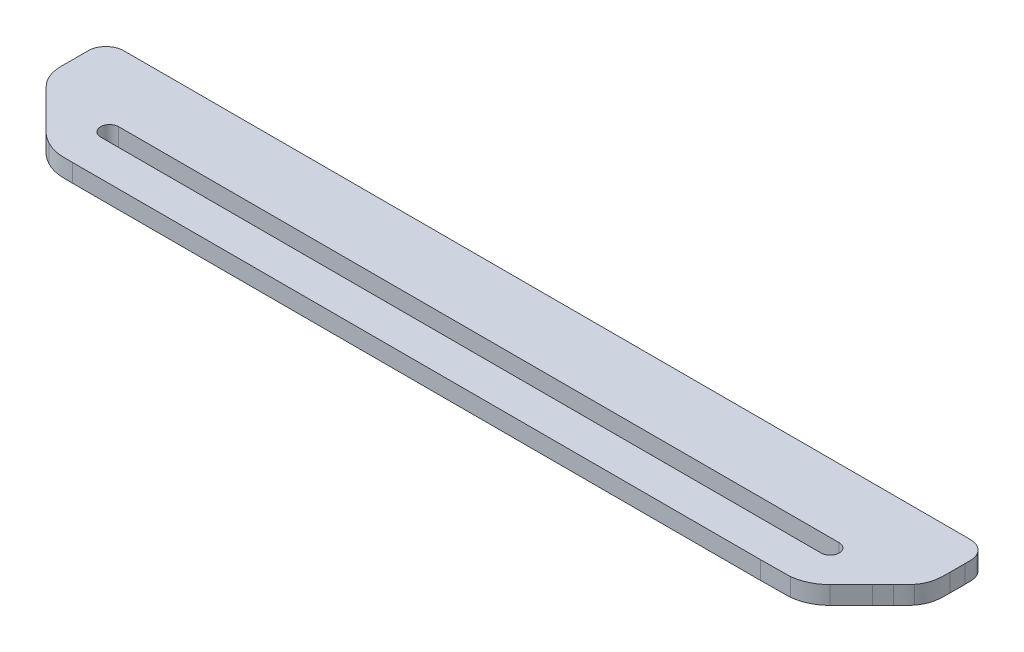
SolidWorks part; units mm, degrees
ref_plane "Front Plane" through (0, 0, 0) normal (0, 0, 1) x (1, 0, 0)
ref_plane "Top Plane" through (0, 0, 0) normal (0, 1, 0) x (1, 0, 0)
ref_plane "Right Plane" through (0, 0, 0) normal (1, 0, 0) x (0, 0, -1)
sketch "Imported Profile" plane through (0, 0, 0) normal (0, 1, 0) x (1, 0, 0)
  spline S0 degree 3 poles (282.8141, 19.2755) (238.813, 19.2755) (194.8191, 19.2755) (150.8184, 19.2755) knots 0 0 0 0 1 1 1 1
  spline S1 degree 3 poles (150.8184, 19.2755) (128.8318, 19.2755) (106.8452, 19.2755) (84.8655, 19.2755) knots 0 0 0 0 1 1 1 1
  spline S2 degree 3 poles (84.8655, 19.2755) (73.9032, 19.2755) (62.9409, 19.2755) (51.9786, 19.2755) knots 0 0 0 0 1 1 1 1
  spline S3 degree 3 poles (51.9786, 19.2755) (46.5009, 19.2755) (41.0163, 19.2755) (35.5386, 19.2755) knots 0 0 0 0 1 1 1 1
  spline S4 degree 3 poles (35.5386, 19.2755) (34.1674, 19.2755) (32.7963, 19.2755) (31.4251, 19.2755) knots 0 0 0 0 1 1 1 1
  spline S5 degree 3 poles (31.4251, 19.2755) (30.743, 19.2755) (30.054, 19.2755) (29.3719, 19.2755) knots 0 0 0 0 1 1 1 1
  spline S6 degree 3 poles (29.3719, 19.2755) (28.676, 19.2755) (28.0283, 19.2615) (27.3737, 18.9309) knots 0 0 0 0 1 1 1 1
  spline S7 degree 3 poles (27.3737, 18.9309) (24.3972, 17.4151) (25.4789, 12.9227) (28.8138, 12.9227) knots 0 0 0 0 1 1 1 1
  spline S8 degree 3 poles (28.8138, 12.9227) (72.8145, 12.9227) (116.8153, 12.9227) (160.816, 12.9227) knots 0 0 0 0 1 1 1 1
  spline S9 degree 3 poles (160.816, 12.9227) (182.7957, 12.9227) (204.7823, 12.9227) (226.7689, 12.9227) knots 0 0 0 0 1 1 1 1
  spline S10 degree 3 poles (226.7689, 12.9227) (237.7312, 12.9227) (248.6867, 12.9227) (259.6489, 12.9227) knots 0 0 0 0 1 1 1 1
  spline S11 degree 3 poles (259.6489, 12.9227) (265.1335, 12.9227) (270.6112, 12.9227) (276.0958, 12.9227) knots 0 0 0 0 1 1 1 1
  spline S12 degree 3 poles (276.0958, 12.9227) (277.4601, 12.9227) (278.8312, 12.9227) (280.2024, 12.9227) knots 0 0 0 0 1 1 1 1
  spline S13 degree 3 poles (280.2024, 12.9227) (280.8914, 12.9227) (281.5735, 12.9227) (282.2557, 12.9227) knots 0 0 0 0 1 1 1 1
  spline S14 degree 3 poles (282.2557, 12.9227) (282.9516, 12.9227) (283.5992, 12.9367) (284.2538, 13.2741) knots 0 0 0 0 1 1 1 1
  spline S15 degree 3 poles (284.2538, 13.2741) (285.5561, 13.9355) (286.2382, 15.3894) (285.9075, 16.8156) knots 0 0 0 0 1 1 1 1
  spline S16 degree 3 poles (285.9075, 16.8156) (285.7285, 17.5873) (285.3838, 18.1317) (284.7568, 18.614) knots 0 0 0 0 1 1 1 1
  spline S17 degree 3 poles (284.7568, 18.614) (284.4603, 18.8413) (284.1573, 19.0067) (283.7991, 19.117) knots 0 0 0 0 1 1 1 1
  spline S18 degree 3 poles (283.7991, 19.117) (283.6406, 19.172) (283.4751, 19.2134) (283.3031, 19.241) knots 0 0 0 0 1 1 1 1
  spline S19 degree 3 poles (283.3031, 19.241) (283.2201, 19.255) (283.1376, 19.2615) (283.0551, 19.2684) knots 0 0 0 0 1 1 1 1
  spline S20 degree 3 poles (283.0551, 19.2684) (283.0151, 19.2684) (282.9721, 19.2755) (282.9381, 19.2755) knots 0 0 0 0 1 1 1 1
  spline S22 degree 3 poles (294.036, 4.8749) (296.5184, 7.3485) (298.9919, 9.8221) (301.4655, 12.3026) knots 0 0 0 0 1 1 1 1
  spline S23 degree 3 poles (301.4655, 12.3026) (302.7057, 13.5359) (303.9391, 14.7762) (305.1793, 16.0095) knots 0 0 0 0 1 1 1 1
  spline S24 degree 3 poles (305.1793, 16.0095) (306.4127, 17.2497) (307.7287, 18.3866) (308.7967, 19.7922) knots 0 0 0 0 1 1 1 1
  spline S25 degree 3 poles (308.7967, 19.7922) (311.3598, 23.1684) (311.3874, 25.8831) (311.3874, 29.8037) knots 0 0 0 0 1 1 1 1
  spline S26 degree 3 poles (311.3874, 29.8037) (311.3874, 31.5538) (311.3924, 33.3039) (311.3924, 35.054) knots 0 0 0 0 1 1 1 1
  spline S27 degree 3 poles (311.3924, 35.054) (311.3924, 36.8248) (311.5164, 38.4784) (310.5587, 40.1665) knots 0 0 0 0 1 1 1 1
  spline S28 degree 3 poles (310.5587, 40.1665) (309.6285, 41.7995) (308.0231, 42.9364) (306.1696, 43.274) knots 0 0 0 0 1 1 1 1
  spline S29 degree 3 poles (306.1696, 43.274) (305.391, 43.4117) (301.7599, 43.3705) (300.9813, 43.3705) knots 0 0 0 0 1 1 1 1
  spline S30 degree 3 poles (300.9813, 43.3705) (297.4811, 43.3705) (293.9809, 43.3705) (290.4807, 43.3705) knots 0 0 0 0 1 1 1 1
  spline S31 degree 3 poles (290.4807, 43.3705) (283.4802, 43.3705) (276.4798, 43.3705) (269.4793, 43.3705) knots 0 0 0 0 1 1 1 1
  spline S32 degree 3 poles (269.4793, 43.3705) (241.3536, 43.3705) (213.2278, 43.3705) (185.1021, 43.3705) knots 0 0 0 0 1 1 1 1
  spline S33 degree 3 poles (185.1021, 43.3705) (128.8643, 43.3705) (72.6197, 43.3705) (16.3751, 43.3705) knots 0 0 0 0 1 1 1 1
  spline S34 degree 3 poles (16.3751, 43.3705) (14.625, 43.3705) (12.8817, 43.3705) (11.1316, 43.3705) knots 0 0 0 0 1 1 1 1
  spline S35 degree 3 poles (11.1316, 43.3705) (10.6424, 43.3705) (6.4187, 43.391) (5.9295, 43.336) knots 0 0 0 0 1 1 1 1
  spline S36 degree 3 poles (5.9295, 43.336) (4.0761, 43.1431) (2.4018, 42.144) (1.3476, 40.6075) knots 0 0 0 0 1 1 1 1
  spline S37 degree 3 poles (1.3476, 40.6075) (0.1349, 38.8367) (0.2383, 37.5138) (0.2383, 35.5501) knots 0 0 0 0 1 1 1 1
  spline S38 degree 3 poles (0.2383, 35.5501) (0.2383, 33.8) (0.2383, 32.0498) (0.2383, 30.2998) knots 0 0 0 0 1 1 1 1
  spline S39 degree 3 poles (0.2383, 30.2998) (0.2383, 28.5565) (0.128, 26.8271) (0.4656, 25.077) knots 0 0 0 0 1 1 1 1
  spline S40 degree 3 poles (0.4656, 25.077) (1.2787, 20.8809) (3.3113, 19.1514) (6.088, 16.3747) knots 0 0 0 0 1 1 1 1
  spline S41 degree 3 poles (6.088, 16.3747) (8.5616, 13.9011) (11.0352, 11.4344) (13.5088, 8.9608) knots 0 0 0 0 1 1 1 1
  spline S42 degree 3 poles (13.5088, 8.9608) (14.7421, 7.7206) (15.9755, 6.4873) (17.2157, 5.247) knots 0 0 0 0 1 1 1 1
  spline S43 degree 3 poles (17.2157, 5.247) (18.4697, 3.993) (19.7926, 2.9112) (21.3774, 2.0775) knots 0 0 0 0 1 1 1 1
  spline S44 degree 3 poles (21.3774, 2.0775) (25.105, 0.1001) (27.6474, 0.2241) (31.6369, 0.2241) knots 0 0 0 0 1 1 1 1
  spline S45 degree 3 poles (31.6369, 0.2241) (35.1302, 0.2241) (38.6304, 0.2241) (42.1237, 0.2241) knots 0 0 0 0 1 1 1 1
  spline S46 degree 3 poles (42.1237, 0.2241) (70.2633, 0.2241) (98.3959, 0.2241) (126.5355, 0.2241) knots 0 0 0 0 1 1 1 1
  spline S47 degree 3 poles (126.5355, 0.2241) (154.6544, 0.2241) (182.7732, 0.2241) (210.899, 0.2241) knots 0 0 0 0 1 1 1 1
  spline S48 degree 3 poles (210.899, 0.2241) (224.9481, 0.2241) (238.9972, 0.2241) (253.0532, 0.2241) knots 0 0 0 0 1 1 1 1
  spline S49 degree 3 poles (253.0532, 0.2241) (260.0743, 0.2241) (267.1023, 0.2241) (274.1234, 0.2241) knots 0 0 0 0 1 1 1 1
  spline S50 degree 3 poles (274.1234, 0.2241) (275.3498, 0.2241) (283.4113, 0.1896) (284.6447, 0.3343) knots 0 0 0 0 1 1 1 1
  spline S51 degree 3 poles (284.6447, 0.3343) (288.2, 0.7477) (291.5073, 2.3462) (294.036, 4.8749) knots 0 0 0 0 1 1 1 1
  point P0 (0, 0)
sketch "Sketch7" plane through (0, 0, 0) normal (0, 1, 0) x (1, 0, 0)
  spline S0 degree 3 poles (2185.0869, 43.3705) (815.4559, 43.3705) (-609.6413, 43.3705) (-1983.6105, 43.3705) knots -11.941861 -11.941861 -11.941861 -11.941861 12.922613 12.922613 12.922613 12.922613 only from (185.1021, 43.3705) to (16.3751, 43.3705) construction
  spline S1 degree 3 poles (2016.3696, 43.3705) (-1638.242, 43.3705) (1665.7336, 43.3705) (-1988.8071, 43.3705) knots -49.681561 -49.681561 -49.681561 -49.681561 50.68105 50.68105 50.68105 50.68105 only from (16.3751, 43.3705) to (11.1316, 43.3705) construction
  spline S2 degree 3 poles (-1988.6659, 66.2223) (2066.8965, 18.2992) (-2049.8173, 70.7656) (2005.6743, 13.5744) knots -5.991431 -5.991431 -5.991431 -5.991431 6.991378 6.991378 6.991378 6.991378 only from (11.1316, 43.3705) to (5.9295, 43.336) construction
  spline S3 degree 3 poles (-1324.375, -1441.7802) (1628.2566, 1258.184) (-1821.7954, -845.051) (1931.0963, 541.8193) knots -15.165681 -15.165681 -15.165681 -15.165681 16.198097 16.198097 16.198097 16.198097 only from (5.9295, 43.336) to (1.3476, 40.6075) construction
  spline S4 degree 3 poles (1649.1907, 1173.8977) (-1586.7379, -1103.3448) (1527.2587, 1250.8841) (-1468.8027, -1320.2836) knots -9.585759 -9.585759 -9.585759 -9.585759 11.043004 11.043004 11.043004 11.043004 only from (1.3476, 40.6075) to (0.2383, 35.5501) construction
  spline S5 degree 3 poles (0.2383, 2035.5443) (0.2383, 685.684) (0.2383, -649.3931) (0.2383, -1969.687) knots -378.838725 -378.838725 -378.838725 -378.838725 384.060926 384.060926 384.060926 384.060926 only from (0.2383, 35.5501) to (0.2383, 30.2998) construction
  spline S6 degree 3 poles (-1988.5091, 236.7279) (1990.8435, -68.7066) (-1990.9289, 123.9944) (1990.6013, -168.5341) knots -15.078506 -15.078506 -15.078506 -15.078506 15.477769 15.477769 15.477769 15.477769 only from (0.2383, 30.2998) to (0.4656, 25.077) construction
  spline S7 degree 3 poles (382.9637, 1988.1252) (-334.0535, -1880.6357) (224.7823, 1927.8988) (-23.4133, -1981.832) knots -7.457803 -7.457803 -7.457803 -7.457803 8.905277 8.905277 8.905277 8.905277 only from (0.4656, 25.077) to (6.088, 16.3747) construction
  spline S8 degree 3 poles (-352.3929, 1975.2221) (-110.9236, -1467.6356) (130.5457, 1492.9362) (372.0149, -1949.8829) knots -48.307999 -48.307999 -48.307999 -48.307999 49.311395 49.311395 49.311395 49.311395 only from (6.088, 16.3747) to (13.5088, 8.9608) construction
  spline S9 degree 3 poles (-929.696, 1772.124) (732.8828, -1510.2223) (-715.8451, 1518.4427) (998.3715, -1736.8599) knots -48.143296 -48.143296 -48.143296 -48.143296 48.934851 48.934851 48.934851 48.934851 only from (13.5088, 8.9608) to (17.2157, 5.247) construction
  spline S10 degree 3 poles (-1928.9645, -441.2517) (1819.6918, 691.9508) (-1754.329, -792.4667) (1853.9595, 802.8604) knots -21.662875 -21.662875 -21.662875 -21.662875 20.540498 20.540498 20.540498 20.540498 only from (17.2157, 5.247) to (21.3774, 2.0775) construction
  spline S11 degree 3 poles (-1422.1306, 1386.1545) (1439.6916, -1289.6249) (-1454.5742, 1200.4298) (1689.5191, -1116.3666) knots -7.595641 -7.595641 -7.595641 -7.595641 8.890729 8.890729 8.890729 8.890729 only from (21.3774, 2.0775) to (31.6369, 0.2241) construction
  spline S12 degree 3 poles (2031.5352, 0.2241) (-2760.9683, 0.2241) (2834.7538, 0.2241) (-1957.8305, 0.2241) knots -56.922687 -56.922687 -56.922687 -56.922687 57.923133 57.923133 57.923133 57.923133 only from (31.6369, 0.2241) to (42.1237, 0.2241) construction
  spline S13 degree 3 poles (-1957.8747, 0.2241) (-390.9578, 0.2241) (559.614, 0.2241) (2126.5297, 0.2241) knots -21.868863 -21.868863 -21.868863 -21.868863 22.868823 22.868823 22.868823 22.868823 only from (42.1237, 0.2241) to (126.5355, 0.2241) construction
  spline S14 degree 3 poles (-1873.4574, 0.2241) (-404.0943, 0.2241) (728.4365, 0.2241) (2210.8836, 0.2241) knots -22.748225 -22.748225 -22.748225 -22.748225 23.631867 23.631867 23.631867 23.631867 only from (126.5355, 0.2241) to (210.899, 0.2241) construction
  spline S15 degree 3 poles (-1789.087, 0.2241) (74.3821, 0.2241) (365.8246, 0.2241) (2253.017, 0.2241) knots -38.266845 -38.266845 -38.266845 -38.266845 38.844326 38.844326 38.844326 38.844326 only from (210.899, 0.2241) to (253.0532, 0.2241) construction
  spline S16 degree 3 poles (2253.0369, 0.2241) (-3468.5225, 0.2241) (3995.6772, 0.2241) (-1725.8198, 0.2241) knots -61.520919 -61.520919 -61.520919 -61.520919 62.520625 62.520625 62.520625 62.520625 only from (253.0532, 0.2241) to (274.1234, 0.2241) construction
  spline S17 degree 3 poles (2273.9287, -26.2695) (-1814.1307, 30.429) (2372.8229, -34.0932) (-1714.9363, 39.0614) knots -4.829714 -4.829714 -4.829714 -4.829714 5.830029 5.830029 5.830029 5.830029 only from (274.1234, 0.2241) to (284.6447, 0.3343) construction
  spline S18 degree 3 poles (1585.5566, 1502.8658) (-1425.4228, -1115.0855) (2233.3061, 643.3772) (-1691.9446, -73.5095) knots -14.483594 -14.483594 -14.483594 -14.483594 15.469417 15.469417 15.469417 15.469417 only from (284.6447, 0.3343) to (294.036, 4.8749) construction
  spline S19 degree 3 poles (-1269.389, -1242.0975) (1344.3218, 778.0888) (-728.9465, -780.6411) (1810.8019, 1323.9507) knots -50.261487 -50.261487 -50.261487 -50.261487 51.446859 51.446859 51.446859 51.446859 only from (294.036, 4.8749) to (301.4655, 12.3026) construction
  spline S20 degree 3 poles (-1266.5699, 1245.7367) (1642.4809, -1448.1452) (-1035.868, 1476.411) (1873.2656, -1217.3305) knots -46.143087 -46.143087 -46.143087 -46.143087 47.140087 47.140087 47.140087 47.140087 only from (301.4655, 12.3026) to (305.1793, 16.0095) construction
  spline S21 degree 3 poles (1566.9987, -1534.9177) (-1037.0997, 1489.8302) (1652.2496, -1453.7665) (-963.028, 1562.6216) knots -15.615814 -15.615814 -15.615814 -15.615814 16.149245 16.149245 16.149245 16.149245 only from (305.1793, 16.0095) to (308.7967, 19.7922) construction
  spline S22 degree 3 poles (-1380.5242, -1050.5835) (1907.0055, 1097.695) (-1193.4079, -1153.7281) (1730.5198, 1436.1044) knots -7.759268 -7.759268 -7.759268 -7.759268 9.282021 9.282021 9.282021 9.282021 only from (308.7967, 19.7922) to (311.3874, 29.8037) construction
  spline S23 degree 3 poles (2281.1756, -267.8731) (-1658.9464, -74.4267) (2281.6945, 139.1934) (-1658.3009, 332.9839) knots -57.673934 -57.673934 -57.673934 -57.673934 58.673 58.673 58.673 58.673 only from (311.3874, 29.8037) to (311.3924, 35.054) construction
  spline S24 degree 3 poles (2279.7849, -315.8526) (-1662.5151, 277.2769) (2290.2385, -178.3193) (-1671.7904, 304.371) knots -11.672913 -11.672913 -11.672913 -11.672913 11.908031 11.908031 11.908031 11.908031 only from (311.3924, 35.054) to (310.5587, 40.1665) construction
  spline S25 degree 3 poles (-1580.7095, 671.0639) (2067.5292, -968.5189) (-1225.851, 1368.8181) (1525.2592, -1534.2437) knots -15.103061 -15.103061 -15.103061 -15.103061 16.108548 16.108548 16.108548 16.108548 only from (310.5587, 40.1665) to (306.1696, 43.274) construction
  spline S26 degree 3 poles (-1691.8083, -46.1812) (2361.8264, 125.6025) (-1754.9275, -31.9187) (2299.6923, 112.1212) knots -6.600491 -6.600491 -6.600491 -6.600491 7.601352 7.601352 7.601352 7.601352 only from (306.1696, 43.274) to (300.9813, 43.3705) construction
  spline S27 degree 3 poles (2300.9725, 43.3705) (964.144, 43.3705) (-372.6845, 43.3705) (-1709.5129, 43.3705) knots -190.464681 -190.464681 -190.464681 -190.464681 191.464906 191.464906 191.464906 191.464906 only from (300.9813, 43.3705) to (290.4807, 43.3705) construction
  spline S28 degree 3 poles (2290.4779, 43.3705) (950.1516, 43.3705) (-390.1747, 43.3705) (-1730.501, 43.3705) knots -95.231934 -95.231934 -95.231934 -95.231934 96.231129 96.231129 96.231129 96.231129 only from (290.4807, 43.3705) to (269.4793, 43.3705) construction
  spline S29 degree 3 poles (2269.4729, 43.3705) (908.9807, 43.3705) (-454.3955, 43.3705) (-1814.8878, 43.3705) knots -23.711529 -23.711529 -23.711529 -23.711529 24.711485 24.711485 24.711485 24.711485 only from (269.4793, 43.3705) to (185.1021, 43.3705) construction
  spline S30 degree 3 poles (185.1021, 43.3705) (128.8643, 43.3705) (72.6197, 43.3705) (16.3751, 43.3705) knots 0 0 0 0 1 1 1 1
  spline S31 degree 3 poles (16.3751, 43.3705) (14.625, 43.3705) (12.8817, 43.3705) (11.1316, 43.3705) knots 0 0 0 0 1 1 1 1
  spline S32 degree 3 poles (11.1316, 43.3705) (10.6424, 43.3705) (6.4187, 43.391) (5.9295, 43.336) knots 0 0 0 0 1 1 1 1
  spline S33 degree 3 poles (5.9295, 43.336) (4.0761, 43.1431) (2.4018, 42.144) (1.3476, 40.6075) knots 0 0 0 0 1 1 1 1
  spline S34 degree 3 poles (1.3476, 40.6075) (0.1349, 38.8367) (0.2383, 37.5138) (0.2383, 35.5501) knots 0 0 0 0 1 1 1 1
  spline S35 degree 3 poles (0.2383, 35.5501) (0.2383, 33.8) (0.2383, 32.0498) (0.2383, 30.2998) knots 0 0 0 0 1 1 1 1
  spline S36 degree 3 poles (0.2383, 30.2998) (0.2383, 28.5565) (0.128, 26.8271) (0.4656, 25.077) knots 0 0 0 0 1 1 1 1
  spline S37 degree 3 poles (0.4656, 25.077) (1.2787, 20.8809) (3.3113, 19.1514) (6.088, 16.3747) knots 0 0 0 0 1 1 1 1
  spline S38 degree 3 poles (6.088, 16.3747) (8.5616, 13.9011) (11.0352, 11.4344) (13.5088, 8.9608) knots 0 0 0 0 1 1 1 1
  spline S39 degree 3 poles (13.5088, 8.9608) (14.7421, 7.7206) (15.9755, 6.4873) (17.2157, 5.247) knots 0 0 0 0 1 1 1 1
  spline S40 degree 3 poles (17.2157, 5.247) (18.4697, 3.993) (19.7926, 2.9112) (21.3774, 2.0775) knots 0 0 0 0 1 1 1 1
  spline S41 degree 3 poles (21.3774, 2.0775) (25.105, 0.1001) (27.6474, 0.2241) (31.6369, 0.2241) knots 0 0 0 0 1 1 1 1
  spline S42 degree 3 poles (31.6369, 0.2241) (35.1302, 0.2241) (38.6304, 0.2241) (42.1237, 0.2241) knots 0 0 0 0 1 1 1 1
  spline S43 degree 3 poles (42.1237, 0.2241) (70.2633, 0.2241) (98.3959, 0.2241) (126.5355, 0.2241) knots 0 0 0 0 1 1 1 1
  spline S44 degree 3 poles (126.5355, 0.2241) (154.6544, 0.2241) (182.7732, 0.2241) (210.899, 0.2241) knots 0 0 0 0 1 1 1 1
  spline S45 degree 3 poles (210.899, 0.2241) (224.9481, 0.2241) (238.9972, 0.2241) (253.0532, 0.2241) knots 0 0 0 0 1 1 1 1
  spline S46 degree 3 poles (253.0532, 0.2241) (260.0743, 0.2241) (267.1023, 0.2241) (274.1234, 0.2241) knots 0 0 0 0 1 1 1 1
  spline S47 degree 3 poles (274.1234, 0.2241) (275.3498, 0.2241) (283.4113, 0.1896) (284.6447, 0.3343) knots 0 0 0 0 1 1 1 1
  spline S48 degree 3 poles (284.6447, 0.3343) (288.2, 0.7477) (291.5073, 2.3462) (294.036, 4.8749) knots 0 0 0 0 1 1 1 1
  spline S49 degree 3 poles (294.036, 4.8749) (296.5184, 7.3485) (298.9919, 9.8221) (301.4655, 12.3026) knots 0 0 0 0 1 1 1 1
  spline S50 degree 3 poles (301.4655, 12.3026) (302.7057, 13.5359) (303.9391, 14.7762) (305.1793, 16.0095) knots 0 0 0 0 1 1 1 1
  spline S51 degree 3 poles (305.1793, 16.0095) (306.4127, 17.2497) (307.7287, 18.3866) (308.7967, 19.7922) knots 0 0 0 0 1 1 1 1
  spline S52 degree 3 poles (308.7967, 19.7922) (311.3598, 23.1684) (311.3874, 25.8831) (311.3874, 29.8037) knots 0 0 0 0 1 1 1 1
  spline S53 degree 3 poles (311.3874, 29.8037) (311.3874, 31.5538) (311.3924, 33.3039) (311.3924, 35.054) knots 0 0 0 0 1 1 1 1
  spline S54 degree 3 poles (311.3924, 35.054) (311.3924, 36.8248) (311.5164, 38.4784) (310.5587, 40.1665) knots 0 0 0 0 1 1 1 1
  spline S55 degree 3 poles (310.5587, 40.1665) (309.6285, 41.7995) (308.0231, 42.9364) (306.1696, 43.274) knots 0 0 0 0 1 1 1 1
  spline S56 degree 3 poles (306.1696, 43.274) (305.391, 43.4117) (301.7599, 43.3705) (300.9813, 43.3705) knots 0 0 0 0 1 1 1 1
  spline S57 degree 3 poles (300.9813, 43.3705) (297.4811, 43.3705) (293.9809, 43.3705) (290.4807, 43.3705) knots 0 0 0 0 1 1 1 1
  spline S58 degree 3 poles (290.4807, 43.3705) (283.4802, 43.3705) (276.4798, 43.3705) (269.4793, 43.3705) knots 0 0 0 0 1 1 1 1
  spline S59 degree 3 poles (269.4793, 43.3705) (241.3536, 43.3705) (213.2278, 43.3705) (185.1021, 43.3705) knots 0 0 0 0 1 1 1 1
sketch "Sketch8" plane through (0, 0, 0) normal (0, 1, 0) x (1, 0, 0)
  line L0 (28.8138, 16.0991) -> (282.813, 16.0991) construction
  line L1 (28.8138, 19.2755) -> (282.813, 19.2755)
  line L2 (28.8138, 12.9227) -> (282.813, 12.9227)
  arc A0 (28.8138, 19.2755) -> (28.8138, 12.9227) centre (28.8138, 16.0991) ccw
  arc A1 (282.813, 12.9227) -> (282.813, 19.2755) centre (282.813, 16.0991) ccw
  point P2 (155.8134, 16.0991)
  point P7 (0, 0)
  point P8 (276.4055, 19.2755)
  point P11 (0, 0)
extrude "Boss-Extrude3" add sketch "Sketch7" along normal blind 6.35
extrude "Cut-Extrude2" cut sketch "Sketch8" along normal through all
